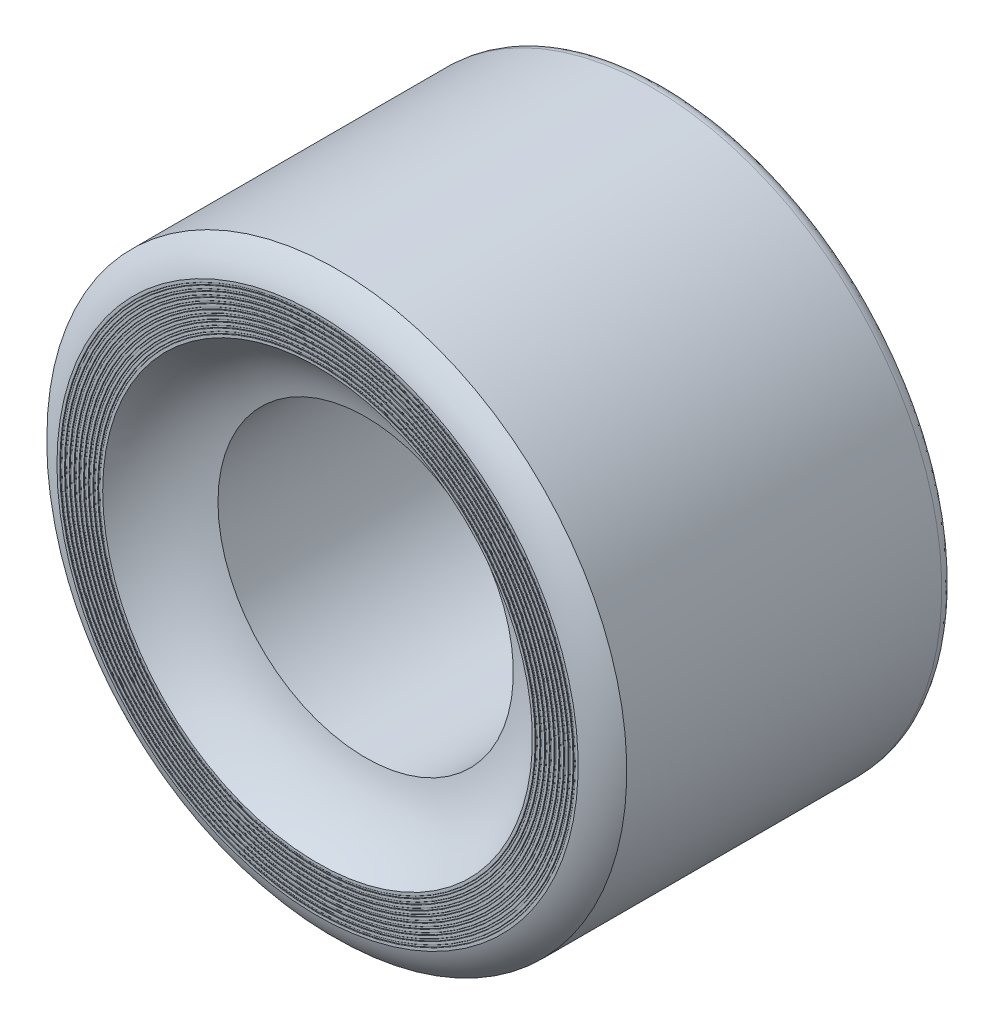
SolidWorks part; units mm, degrees
ref_plane "Front Plane" through (0, 0, 0) normal (0, 0, 1) x (1, 0, 0)
ref_plane "Top Plane" through (0, 0, 0) normal (0, 1, 0) x (1, 0, 0)
ref_plane "Right Plane" through (0, 0, 0) normal (1, 0, 0) x (0, 0, -1)
ref_plane "Plane1" through (0, 0, 0) normal (0, -1, 0) x (1, 0, 0)
sketch "Sketch1" plane through (0, 0, 0) normal (0, -1, 0) x (1, 0, 0)
  line L0 (34.97, 26) -> (34.97, 26.05)
  line L1 (34.92, 26.1) -> (34.57, 26.1)
  line L2 (34.52, 26.05) -> (34.52, 26)
  line L3 (34.52, 26) -> (34.27, 26)
  line L4 (34.27, 26) -> (34.27, 26.05)
  line L5 (34.22, 26.1) -> (33.87, 26.1)
  line L6 (33.82, 26.05) -> (33.82, 26)
  line L7 (33.82, 26) -> (33.57, 26)
  line L8 (33.57, 26) -> (33.57, 26.05)
  line L9 (33.52, 26.1) -> (33.17, 26.1)
  line L10 (33.12, 26.05) -> (33.12, 26)
  line L11 (33.12, 26) -> (32.87, 26)
  line L12 (32.87, 26) -> (32.87, 26.05)
  line L13 (32.82, 26.1) -> (32.47, 26.1)
  line L14 (32.42, 26.05) -> (32.42, 26)
  line L15 (32.42, 26) -> (32.17, 26)
  line L16 (32.17, 26) -> (32.17, 26.05)
  line L17 (32.12, 26.1) -> (31.72, 26.1)
  line L18 (21.8, 19) -> (21.8, -19)
  line L19 (42.8, -23.25) -> (42.8, 23.25)
  line L20 (38.47, 26.1) -> (38.07, 26.1)
  line L21 (38.02, 26.05) -> (38.02, 26)
  line L22 (38.02, 26) -> (37.77, 26)
  line L23 (37.77, 26) -> (37.77, 26.05)
  line L24 (37.72, 26.1) -> (37.37, 26.1)
  line L25 (37.32, 26.05) -> (37.32, 26)
  line L26 (37.32, 26) -> (37.07, 26)
  line L27 (37.07, 26) -> (37.07, 26.05)
  line L28 (37.02, 26.1) -> (36.67, 26.1)
  line L29 (36.62, 26.05) -> (36.62, 26)
  line L30 (36.62, 26) -> (36.37, 26)
  line L31 (36.37, 26) -> (36.37, 26.05)
  line L32 (36.32, 26.1) -> (35.97, 26.1)
  line L33 (35.92, 26.05) -> (35.92, 26)
  line L34 (35.92, 26) -> (35.67, 26)
  line L35 (35.67, 26) -> (35.67, 26.05)
  line L36 (35.62, 26.1) -> (35.27, 26.1)
  line L37 (35.22, 26.05) -> (35.22, 26)
  line L38 (35.22, 26) -> (34.97, 26)
  line L39 (0, 26.2591) -> (0, -26.2591) construction
  arc A0 (34.97, 26.05) -> (34.92, 26.1) centre (34.92, 26.05) ccw
  arc A1 (34.57, 26.1) -> (34.52, 26.05) centre (34.57, 26.05) ccw
  arc A2 (34.27, 26.05) -> (34.22, 26.1) centre (34.22, 26.05) ccw
  arc A3 (33.87, 26.1) -> (33.82, 26.05) centre (33.87, 26.05) ccw
  arc A4 (33.57, 26.05) -> (33.52, 26.1) centre (33.52, 26.05) ccw
  arc A5 (33.17, 26.1) -> (33.12, 26.05) centre (33.17, 26.05) ccw
  arc A6 (32.87, 26.05) -> (32.82, 26.1) centre (32.82, 26.05) ccw
  arc A7 (32.47, 26.1) -> (32.42, 26.05) centre (32.47, 26.05) ccw
  arc A8 (32.17, 26.05) -> (32.12, 26.1) centre (32.12, 26.05) ccw
  arc A9 (42.8, 23.25) -> (38.47, 26.1) centre (35.4674, 16.8239) ccw
  arc A10 (38.07, 26.1) -> (38.02, 26.05) centre (38.07, 26.05) ccw
  arc A11 (37.77, 26.05) -> (37.72, 26.1) centre (37.72, 26.05) ccw
  arc A12 (37.37, 26.1) -> (37.32, 26.05) centre (37.37, 26.05) ccw
  arc A13 (37.07, 26.05) -> (37.02, 26.1) centre (37.02, 26.05) ccw
  arc A14 (36.67, 26.1) -> (36.62, 26.05) centre (36.67, 26.05) ccw
  arc A15 (36.37, 26.05) -> (36.32, 26.1) centre (36.32, 26.05) ccw
  arc A16 (35.97, 26.1) -> (35.92, 26.05) centre (35.97, 26.05) ccw
  arc A17 (35.67, 26.05) -> (35.62, 26.1) centre (35.62, 26.05) ccw
  arc A18 (35.27, 26.1) -> (35.22, 26.05) centre (35.27, 26.05) ccw
  spline S0 degree 3 poles (21.8, 19) (26.0319, 20.0324) (29.3386, 22.3991) (31.72, 26.1) knots 0 0 0 0 1 1 1 1
  spline S1 degree 3 poles (42.8, -23.25) (42.8, -25.6516) (39.567, -25.297) (35.6351, -25.9521) (33.4241, -26.6363) (28.3003, -23.0892) (26.0862, -18.0309) (21.8, -19) knots 0 0 0 0 0.25 0.25 0.5 0.5 1 1 1 1
  dimension "D5" = 0.05
  dimension "D12" = 0.35
  dimension "D14" = 9.75
  dimension "D1" = 52.5181
  dimension "D2" = 21.8
  dimension "D3" = 38
  dimension "D4" = 46.5
  dimension "D6" = 0.4
  dimension "D7" = 0.05
  dimension "D8" = 0.25
  dimension "D9" = 9.92
  dimension "D10" = 7.1
  dimension "D11" = 0.05
  dimension "D13" = 49.35
  dimension "D15" = 21
  dimension "D16" = 4.33
  dimension "D17" = 0.4
  dimension "D18" = 0.45
revolve "Revolve1" add sketch "Sketch1" angle 360 about L39
